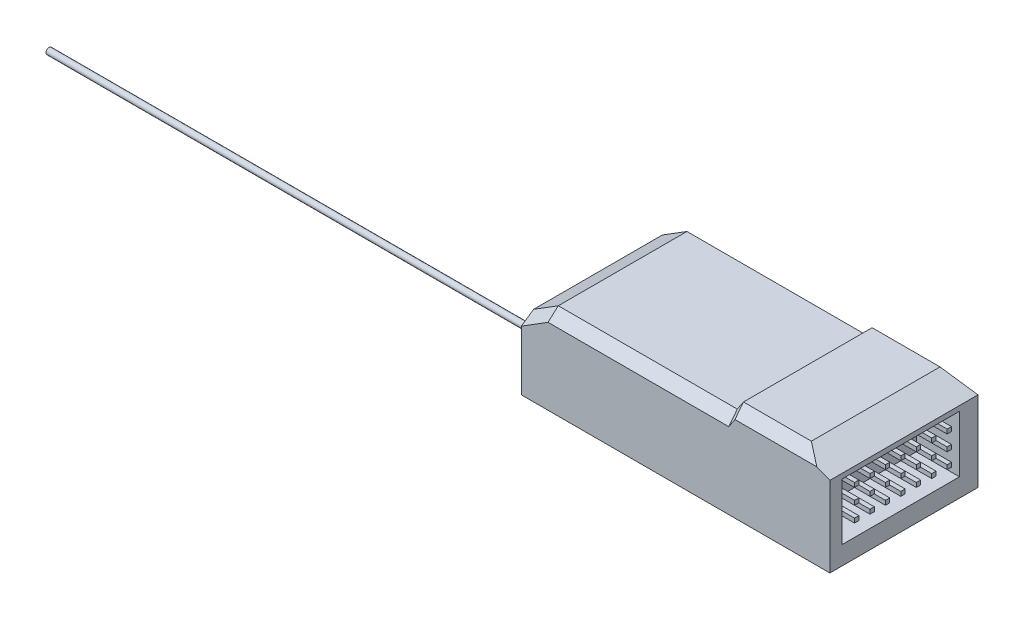
SolidWorks part; units mm, degrees
ref_plane "Front Plane" through (0, 0, 0) normal (0, 0, 1) x (1, 0, 0)
ref_plane "Top Plane" through (0, 0, 0) normal (0, 1, 0) x (1, 0, 0)
ref_plane "Right Plane" through (0, 0, 0) normal (1, 0, 0) x (0, 0, -1)
sketch "Sketch1" plane through (0, 0, 0) normal (0, 0, 1) x (1, 0, 0)
  line L0 (0, 0) -> (0, 11)
  line L1 (0, 11) -> (4, 13.5)
  line L2 (4, 13.5) -> (33, 13.5)
  line L3 (33, 13.5) -> (34, 15)
  line L4 (34, 15) -> (45, 15)
  line L5 (45, 15) -> (50, 13)
  line L6 (50, 13) -> (50, 0)
  line L7 (50, 0) -> (0, 0)
  point P3 (0, 5.5)
  dimension "D1" = 15
  dimension "D2" = 50
  dimension "D3" = 13.5
  dimension "D4" = 17
  dimension "D5" = 13
  dimension "D6" = 11
  dimension "D7" = 5
  dimension "D8" = 11
  dimension "D9" = 4
extrude "Boss-Extrude1" add sketch "Sketch1" along normal blind 24
sketch "Sketch2" plane through (50, 0, 0) normal (1, 0, 0) x (0, 0, -1)
  line L0 (-24, 0) -> (-24, 13) construction
  line L1 (-22, 12.2) -> (-3, 12.2)
  line L2 (-22, 12.2) -> (-22, 3)
  line L3 (-22, 3) -> (-3, 3)
  line L4 (-3, 12.2) -> (-3, 3)
  line L5 (0, 0) -> (0, 13) construction
  line L6 (-24, 0) -> (0, 0) construction
  dimension "D1" = 9.2
  dimension "D2" = 19
  dimension "D3" = 2
  dimension "D4" = 3
  dimension "D5" = 3
extrude "Cut-Extrude1" cut sketch "Sketch2" against normal blind 7
sketch "Sketch3" plane through (43, 0, 0) normal (1, 0, 0) x (0, 0, -1)
  line L0 (-22, 3) -> (-3, 3) construction
  line L1 (-20, 5) -> (-19.3, 5)
  line L2 (-20, 5) -> (-20, 5.7)
  line L3 (-20, 5.7) -> (-19.3, 5.7)
  line L4 (-19.3, 5) -> (-19.3, 5.7)
  line L5 (-22, 12.2) -> (-22, 3) construction
  dimension "D1" = 0.7
  dimension "D2" = 0.7
  dimension "D3" = 2
  dimension "D4" = 2
extrude "Boss-Extrude2" add sketch "Sketch3" along normal blind 7
pattern_linear "LPattern1" count 7 spacing 2.5 along (0, 0, -1) count 3 spacing 2.5 along (0, 1, 0) of "Boss-Extrude2"
chamfer "Chamfer1" distance 2 angle 30 8 edges at (39.5, 15, 0) (33.5, 14.25, 0) (18.5, 13.5, 0) (2, 12.25, 0) (39.5, 15, 24) (33.5, 14.25, 24) (2, 12.25, 24) (18.5, 13.5, 24)
sketch "Sketch5" plane through (0, 0, 0) normal (-1, 0, 0) x (0, 0, 1)
  line L0 (24, 0) -> (0, 0) construction
  line L1 (24, 9.6383) -> (24, 0) construction
  circle A0 centre (19.5, 5.5) radius 1.5
  dimension "D1" = 3
  dimension "D3" = 4.5
  dimension "D2" = 5.5
extrude "Boss-Extrude3" add sketch "Sketch5" along normal blind 1
sketch "Sketch6" plane through (-1, 0, 0) normal (-1, 0, 0) x (0, 0, 1)
  circle A0 centre (19.5, 5.5) radius 0.5
  dimension "D1" = 1
extrude "Boss-Extrude4" add sketch "Sketch6" along normal blind 80
